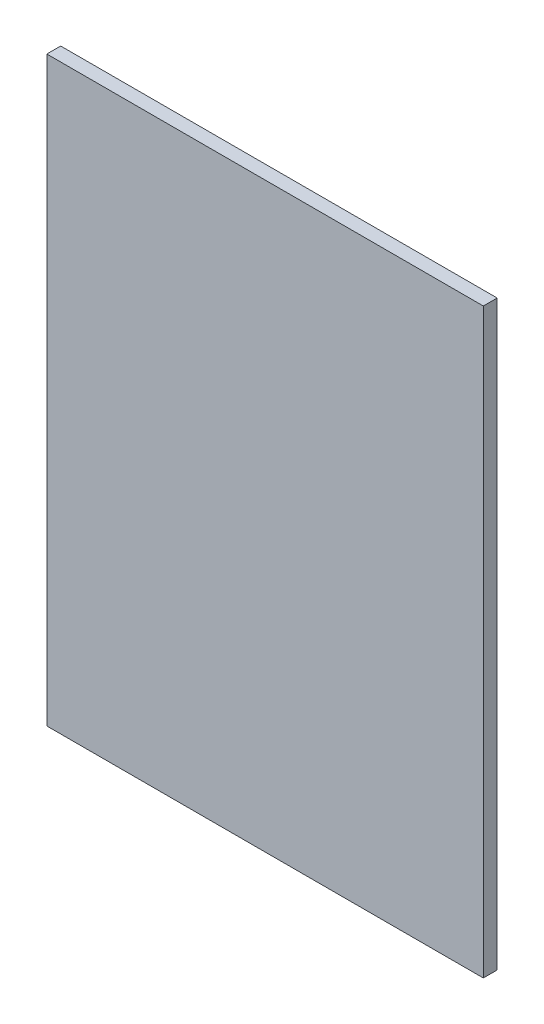
SolidWorks part; units mm, degrees
ref_plane "Alzado" through (0, 0, 0) normal (0, 0, 1) x (1, 0, 0)
ref_plane "Planta" through (0, 0, 0) normal (0, 1, 0) x (1, 0, 0)
ref_plane "Vista lateral" through (0, 0, 0) normal (1, 0, 0) x (0, 0, -1)
sketch "Croquis1" plane through (0, 0, 0) normal (0, 0, 1) x (1, 0, 0)
  line L1 (0, 0) -> (150, 0)
  line L2 (0, 0) -> (0, 200)
  line L3 (0, 200) -> (150, 200)
  line L4 (150, 0) -> (150, 200)
  dimension "D1" = 200
  dimension "D2" = 150
extrude "Saliente-Extruir1" add sketch "Croquis1" along normal blind 4.7625
